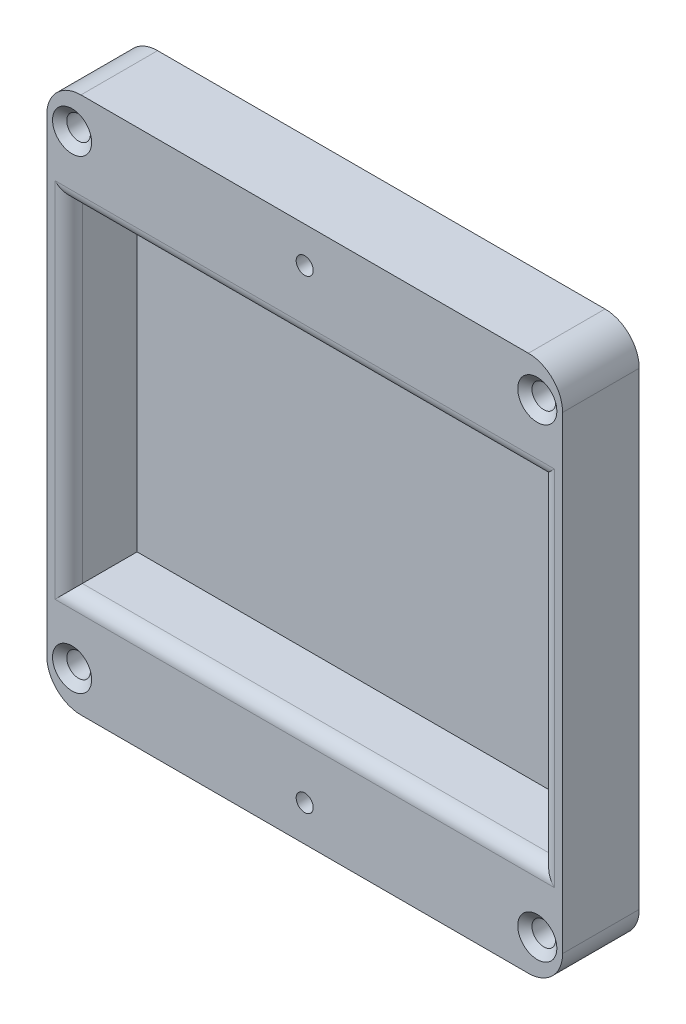
SolidWorks part; units mm, degrees
ref_plane "Front Plane" through (0, 0, 0) normal (0, 0, 1) x (1, 0, 0)
ref_plane "Top Plane" through (0, 0, 0) normal (0, 1, 0) x (1, 0, 0)
ref_plane "Right Plane" through (0, 0, 0) normal (1, 0, 0) x (0, 0, -1)
sketch "Sketch1" plane through (0, 0, 0) normal (0, 0, 1) x (1, 0, 0)
  line L1 (-37.7, -39.25) -> (37.7, -39.25)
  line L2 (-37.7, -39.25) -> (-37.7, 39.25)
  line L3 (-37.7, 39.25) -> (37.7, 39.25)
  line L4 (37.7, -39.25) -> (37.7, 39.25)
  line L5 (-37.7, -39.25) -> (37.7, 39.25) construction
  line L6 (-37.7, 39.25) -> (37.7, -39.25) construction
  point P0 (0, 0)
  dimension "D1" = 75.4
  dimension "D2" = 78.5
extrude "Boss-Extrude1" add sketch "Sketch1" along normal blind 11.2
sketch "Sketch2" plane through (0, 0, 11.2) normal (0, 0, 1) x (1, 0, 0)
  line L0 (0, 39.25) -> (0, -39.25) construction
  line L1 (37.7, 39.25) -> (-37.7, 39.25) construction
  line L2 (-37.7, -39.25) -> (37.7, -39.25) construction
  line L3 (-37.7, 0) -> (37.7, 0) construction
  line L4 (-37.7, 39.25) -> (-37.7, -39.25) construction
  line L5 (37.7, -39.25) -> (37.7, 39.25) construction
  line L7 (-34.5, 24.5) -> (34.5, 24.5)
  line L8 (-34.5, 24.5) -> (-34.5, -24.5)
  line L9 (-34.5, -24.5) -> (34.5, -24.5)
  line L10 (34.5, 24.5) -> (34.5, -24.5)
  line L11 (-34.5, 24.5) -> (34.5, -24.5) construction
  line L12 (-34.5, -24.5) -> (34.5, 24.5) construction
  point P12 (0, 0)
  dimension "D1" = 49
  dimension "D2" = 69
extrude "Cut-Extrude1" cut sketch "Sketch2" against normal blind 10
fillet "Fillet2" radius 2 4 edges at (-34.5, 0, 11.2) (0, -24.5, 11.2) (34.5, 0, 11.2) (0, 24.5, 11.2)
sketch "Sketch3" plane through (0, 0, 11.2) normal (0, 0, 1) x (1, 0, 0)
  line L0 (-37.7, 0) -> (37.7, 0) construction
  line L1 (-37.7, 39.25) -> (-37.7, -39.25) construction
  line L2 (37.7, -39.25) -> (37.7, 39.25) construction
  line L3 (0, 39.25) -> (0, 26.5) construction
  line L4 (37.7, 39.25) -> (-37.7, 39.25) construction
  line L5 (-36.5, 26.5) -> (36.5, 26.5) construction
  circle A0 centre (0, 34) radius 1.2446
  circle A1 centre (0, -34) radius 1.2446
  dimension "D1" = 34
extrude "Cut-Extrude2" cut sketch "Sketch3" against normal blind 10
fillet "Fillet3" radius 5 4 edges at (-37.7, 39.25, 5.6) (-37.7, -39.25, 5.6) (37.7, -39.25, 5.6) (37.7, 39.25, 5.6)
sketch "Sketch6" plane through (0, 0, 11.2) normal (0, 0, 1) x (1, 0, 0)
  line L1 (34, -34) -> (-34, -34)
  line L2 (34, -34) -> (34, 34)
  line L3 (34, 34) -> (-34, 34)
  line L4 (-34, -34) -> (-34, 34)
  line L5 (34, -34) -> (-34, 34) construction
  line L6 (34, 34) -> (-34, -34) construction
  point P0 (0, 0)
  point P8 (0, -34)
hole_wizard "CSK for #4 Flat Head Machine Screw (100)1" positions "Sketch7" profile "Sketch8" countersink size "#4" standard "ANSI Inch" end condition through all
sketch "Sketch7" plane through (0, 0, 11.2) normal (0, 0, 1) x (1, 0, 0)
  point P0 (34, -34)
  point P3 (-34, -34)
  point P6 (-34, 34)
  point P9 (34, 34)
sketch "Sketch8" plane through (34, -34, 11.2) normal (1, 0, 0) x (0, -1, 0)
  line L0 (0, 0) -> (0, 11.2)
  line L1 (0, 11.2) -> (1.7272, 11.2)
  line L2 (1.7272, 11.2) -> (1.7272, 0.9484)
  line L3 (1.7272, 0.9484) -> (2.8575, 0)
  line L5 (2.8575, 0) -> (0, 0)
  line L6 (-1.7272, 0.9484) -> (-2.8575, 0) construction
  line L11 (0, -6.35) -> (0, 107.95) construction
  dimension "Thru Hole Dia." = 3.4544
  dimension "Thru Hole Depth" = 11.2
  dimension "Near C'Sink Dia." = 5.715
  dimension "Near C'Sink Angle" = 100
equation "\"Box_Width\"= 79.93mm"
equation "\"Box_Length\"= 129.93mm"
equation "\"LoggerMount_Width\"= 26.04mm"
equation "\"LoggerMount_Length\"= 45.85mm"
equation "\"LoggerMount_Hole\"= 2.5mm"
equation "\"Box_Hole\"= 4mm"
equation "\"D2@Sketch1\"=\"Lid_Width\""
equation "\"Lid_Length\"= 128mm"
equation "\"Lid_Width\"= 78.5mm"
